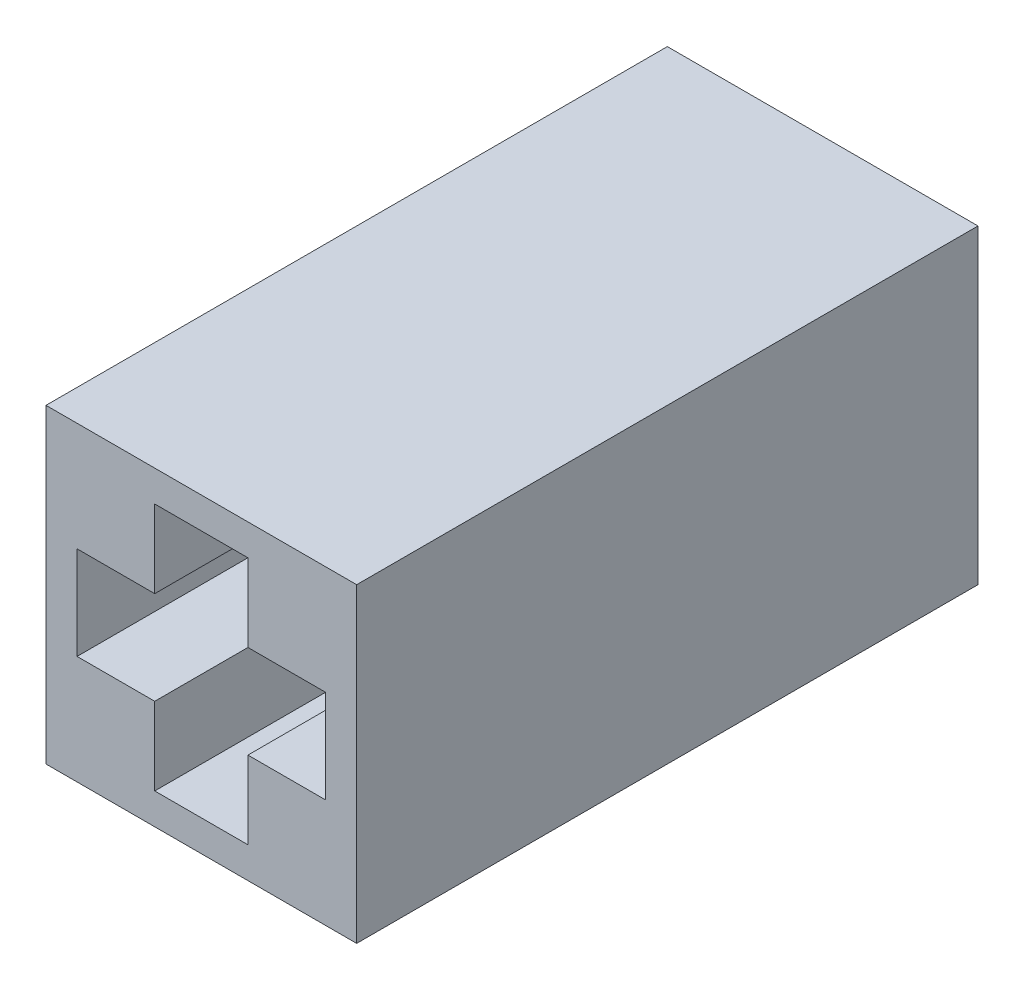
SolidWorks part; units mm, degrees
ref_plane "Front Plane" through (0, 0, 0) normal (0, 0, 1) x (1, 0, 0)
ref_plane "Top Plane" through (0, 0, 0) normal (0, 1, 0) x (1, 0, 0)
ref_plane "Right Plane" through (0, 0, 0) normal (1, 0, 0) x (0, 0, -1)
sketch "Sketch1" plane through (0, 0, 0) normal (0, 0, 1) x (1, 0, 0)
  line L1 (-25, 25) -> (25, 25)
  line L2 (-25, 25) -> (-25, -25)
  line L3 (-25, -25) -> (25, -25)
  line L4 (25, 25) -> (25, -25)
  line L5 (-25, 25) -> (25, -25) construction
  line L6 (-25, -25) -> (25, 25) construction
  point P0 (0, 0)
  dimension "D1" = 50
  dimension "D2" = 50
extrude "Boss-Extrude1" add sketch "Sketch1" against normal blind 100
sketch "Sketch2" plane through (0, 0, 0) normal (0, 0, 1) x (1, 0, 0)
  line L0 (7.5, 7.5) -> (20, 7.5)
  line L1 (-7.5, 20) -> (7.5, 20)
  line L2 (-7.5, 20) -> (-7.5, 7.5)
  line L3 (-7.5, -20) -> (7.5, -20)
  line L4 (7.5, 20) -> (7.5, 7.5)
  line L7 (-20, 7.5) -> (-7.5, 7.5)
  line L8 (-20, 7.5) -> (-20, -7.5)
  line L9 (-20, -7.5) -> (-7.5, -7.5)
  line L10 (20, 7.5) -> (20, -7.5)
  line L13 (-7.5, -7.5) -> (-7.5, -20)
  line L16 (7.5, -7.5) -> (20, -7.5)
  line L19 (7.5, -7.5) -> (7.5, -20)
  point P0 (0, 0)
  point P6 (0, 0)
  dimension "D1" = 15
  dimension "D2" = 15
  dimension "D3" = 40
  dimension "D4" = 40
extrude "Cut-Extrude1" cut sketch "Sketch2" against normal blind 400
